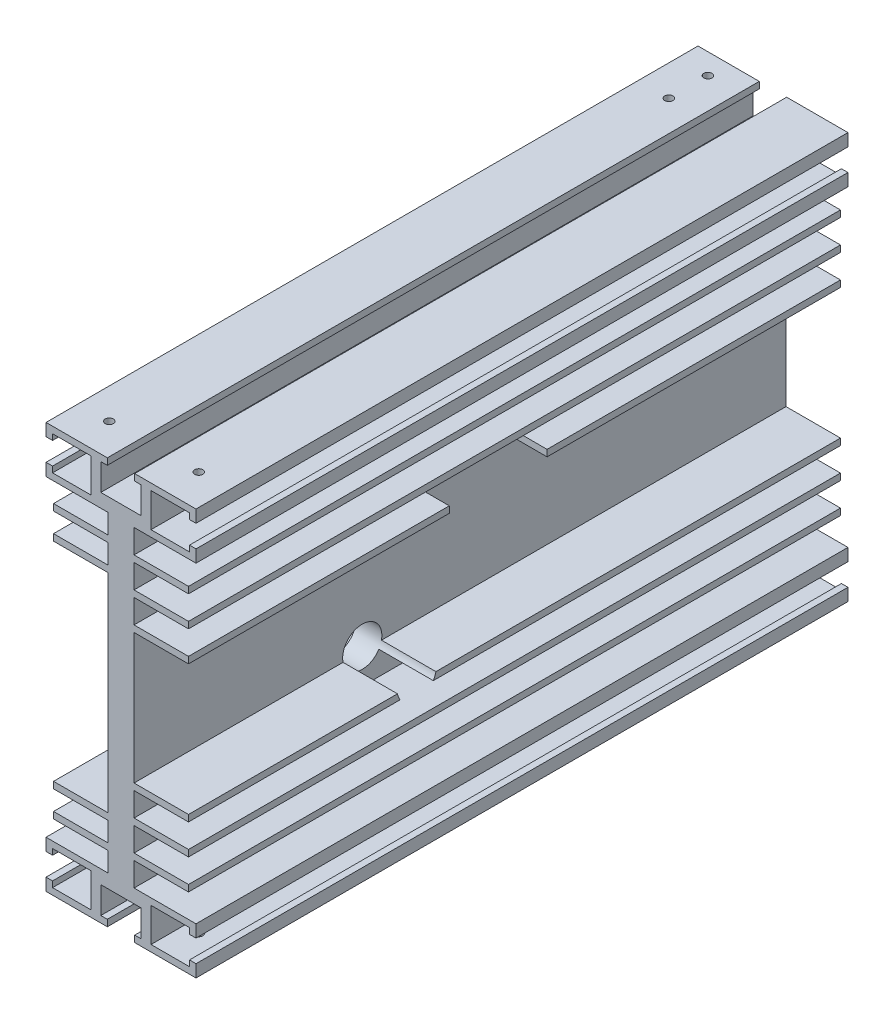
SolidWorks part; units mm, degrees
material "Alumina"
ref_plane "Plano frontal" through (0, 0, 0) normal (0, 0, 1) x (1, 0, 0)
ref_plane "Plano superior" through (0, 0, 0) normal (0, 1, 0) x (1, 0, 0)
ref_plane "Plano direito" through (0, 0, 0) normal (1, 0, 0) x (0, 0, -1)
sketch "Esboço1" plane through (0, 0, 0) normal (0, 0, 1) x (1, 0, 0)
  line L0 (-54.7403, -0.6) -> (-54.7403, 63.2)
  line L1 (-44.5403, -20.8) -> (-44.5403, -29)
  line L2 (-44.5403, -29) -> (-46.5403, -29)
  line L3 (-46.5403, -29) -> (-46.5403, -31)
  line L4 (-46.5403, -31) -> (-27.7403, -31)
  line L5 (-27.7403, -31) -> (-27.7403, -27.2)
  line L6 (-27.7403, -27.2) -> (-29.7403, -27.2)
  line L7 (-29.7403, -27.2) -> (-29.7403, -29)
  line L8 (-29.7403, -29) -> (-41.5403, -29)
  line L9 (-41.5403, -29) -> (-41.5403, -18.6)
  line L10 (-41.5403, -18.6) -> (-29.7403, -18.6)
  line L11 (-29.7403, -18.6) -> (-29.7403, -20.4)
  line L12 (-29.7403, -20.4) -> (-27.7403, -20.4)
  line L13 (-27.7403, -20.4) -> (-27.7403, -16.6)
  line L14 (-27.7403, -16.6) -> (-46.7403, -16.6)
  line L15 (-46.7403, -7.3) -> (-46.7403, 0)
  line L16 (-46.7403, -7.3) -> (-30.0403, -7.3)
  line L17 (-30.0403, -7.3) -> (-30.0403, -9.3)
  line L18 (-30.0403, -9.3) -> (-46.7403, -9.3)
  line L19 (-46.7403, -16.6) -> (-46.7403, -9.3)
  line L20 (-46.7403, 0) -> (-30.0403, 0)
  line L21 (-30.0403, 0) -> (-30.0403, 2)
  line L22 (-30.0403, 2) -> (-46.7403, 2)
  line L23 (-46.7403, 2) -> (-46.7403, 9.3)
  line L24 (-46.7403, 9.3) -> (-30.0403, 9.3)
  line L25 (-30.0403, 9.3) -> (-30.0403, 11.3)
  line L26 (-30.0403, 11.3) -> (-46.7403, 11.3)
  line L27 (-46.7403, 11.3) -> (-46.7403, 51.3)
  line L29 (-56.9403, -20.8) -> (-44.5403, -20.8)
  line L30 (-56.9403, 83.4) -> (-56.9403, 91.6)
  line L31 (-56.9403, 91.6) -> (-54.9403, 91.6)
  line L32 (-54.9403, 91.6) -> (-54.9403, 93.6)
  line L33 (-54.9403, 93.6) -> (-73.7403, 93.6)
  line L34 (-73.7403, 93.6) -> (-73.7403, 89.8)
  line L35 (-71.4403, -0.6) -> (-54.7403, -0.6)
  line L36 (-71.4403, -2.6) -> (-71.4403, -0.6)
  line L37 (-54.7403, -2.6) -> (-71.4403, -2.6)
  line L38 (-54.7403, -16.6) -> (-54.7403, -10.6)
  line L39 (-71.4403, -10.6) -> (-54.7403, -10.6)
  line L40 (-71.4403, -8.6) -> (-71.4403, -10.6)
  line L41 (-54.7403, -8.6) -> (-71.4403, -8.6)
  line L42 (-54.7403, -8.6) -> (-54.7403, -2.6)
  line L43 (-73.7403, -16.6) -> (-54.7403, -16.6)
  line L44 (-73.7403, -20.4) -> (-73.7403, -16.6)
  line L45 (-71.7403, -20.4) -> (-73.7403, -20.4)
  line L46 (-71.7403, -18.6) -> (-71.7403, -20.4)
  line L47 (-59.9403, -18.6) -> (-71.7403, -18.6)
  line L48 (-59.9403, -29) -> (-59.9403, -18.6)
  line L49 (-71.7403, -29) -> (-59.9403, -29)
  line L50 (-71.7403, -27.2) -> (-71.7403, -29)
  line L51 (-73.7403, -27.2) -> (-71.7403, -27.2)
  line L52 (-73.7403, -31) -> (-73.7403, -27.2)
  line L53 (-54.9403, -31) -> (-73.7403, -31)
  line L54 (-54.9403, -29) -> (-54.9403, -31)
  line L55 (-56.9403, -29) -> (-54.9403, -29)
  line L56 (-56.9403, -20.8) -> (-56.9403, -29)
  line L57 (-73.7403, 89.8) -> (-71.7403, 89.8)
  line L58 (-71.7403, 89.8) -> (-71.7403, 91.6)
  line L59 (-71.7403, 91.6) -> (-59.9403, 91.6)
  line L60 (-59.9403, 91.6) -> (-59.9403, 81.2)
  line L61 (-59.9403, 81.2) -> (-71.7403, 81.2)
  line L62 (-71.7403, 81.2) -> (-71.7403, 83)
  line L63 (-71.7403, 83) -> (-73.7403, 83)
  line L64 (-73.7403, 83) -> (-73.7403, 79.2)
  line L65 (-73.7403, 79.2) -> (-54.7403, 79.2)
  line L66 (-54.7403, 71.2) -> (-54.7403, 65.2)
  line L67 (-54.7403, 71.2) -> (-71.4403, 71.2)
  line L68 (-71.4403, 71.2) -> (-71.4403, 73.2)
  line L69 (-71.4403, 73.2) -> (-54.7403, 73.2)
  line L70 (-54.7403, 79.2) -> (-54.7403, 73.2)
  line L71 (-54.7403, 65.2) -> (-71.4403, 65.2)
  line L72 (-71.4403, 65.2) -> (-71.4403, 63.2)
  line L73 (-71.4403, 63.2) -> (-54.7403, 63.2)
  line L74 (-56.9403, 83.4) -> (-44.5403, 83.4)
  line L75 (-30.0403, 51.3) -> (-46.7403, 51.3)
  line L76 (-30.0403, 53.3) -> (-30.0403, 51.3)
  line L77 (-46.7403, 53.3) -> (-30.0403, 53.3)
  line L78 (-46.7403, 60.6) -> (-46.7403, 53.3)
  line L79 (-30.0403, 60.6) -> (-46.7403, 60.6)
  line L80 (-30.0403, 62.6) -> (-30.0403, 60.6)
  line L81 (-46.7403, 62.6) -> (-30.0403, 62.6)
  line L82 (-46.7403, 79.2) -> (-46.7403, 71.9)
  line L83 (-30.0403, 71.9) -> (-46.7403, 71.9)
  line L84 (-30.0403, 69.9) -> (-30.0403, 71.9)
  line L85 (-46.7403, 69.9) -> (-30.0403, 69.9)
  line L86 (-46.7403, 69.9) -> (-46.7403, 62.6)
  line L87 (-27.7403, 79.2) -> (-46.7403, 79.2)
  line L88 (-27.7403, 83) -> (-27.7403, 79.2)
  line L89 (-29.7403, 83) -> (-27.7403, 83)
  line L90 (-29.7403, 81.2) -> (-29.7403, 83)
  line L91 (-41.5403, 81.2) -> (-29.7403, 81.2)
  line L92 (-41.5403, 91.6) -> (-41.5403, 81.2)
  line L93 (-29.7403, 91.6) -> (-41.5403, 91.6)
  line L94 (-29.7403, 89.8) -> (-29.7403, 91.6)
  line L95 (-27.7403, 89.8) -> (-29.7403, 89.8)
  line L96 (-27.7403, 93.6) -> (-27.7403, 89.8)
  line L97 (-46.5403, 93.6) -> (-27.7403, 93.6)
  line L98 (-46.5403, 91.6) -> (-46.5403, 93.6)
  line L99 (-44.5403, 91.6) -> (-46.5403, 91.6)
  line L100 (-44.5403, 83.4) -> (-44.5403, 91.6)
  dimension "D1" = 2
  dimension "D2" = 3.8
  dimension "D3" = 2
  dimension "D4" = 18.8
  dimension "D5" = 3
  dimension "D6" = 2
  dimension "D7" = 2
  dimension "D8" = 2
  dimension "D9" = 3.8
  dimension "D10" = 4.2
  dimension "D11" = 19
  dimension "D12" = 16.7
  dimension "D13" = 7.3
  dimension "D14" = 2
  dimension "D15" = 6
  dimension "D16" = 6
  dimension "D17" = 10.4
  dimension "D18" = 40
  dimension "D19" = 63.8
extrude "Ressalto-extrusão1" add sketch "Esboço1" along normal blind 200
ref_plane "Plano1" through (0, 0, 100) normal (0, 0, 1) x (1, 0, 0)
ref_plane "Plano2" through (0, 31.3, 0) normal (0, -1, 0) x (1, 0, 0)
sketch "Esboço4" plane through (-54.7403, 0, 0) normal (-1, 0, 0) x (0, 0, 1)
  line L0 (200, 93.6) -> (0, 93.6) construction
  line L1 (0, 63.2) -> (0, -0.6) construction
  circle A0 centre (104, 50.1) radius 1.825
  dimension "D1" = 43.5
  dimension "D2" = 104
extrude "Corte-extrusão3" cut sketch "Esboço4" against normal up to next
sketch "Esboço6" plane through (-54.7403, 0, 0) normal (-1, 0, 0) x (0, 0, 1)
  line L0 (200, -31) -> (0, -31) construction
  line L3 (0, 63.2) -> (0, -0.6) construction
  circle A0 centre (130, 12.5) radius 6.0125
  dimension "D1" = 12.025
  dimension "D2" = 43.5
  dimension "D3" = 130
extrude "Corte-extrusão5" cut sketch "Esboço6" against normal up to next
hole_wizard "Broca de rosquear para tarraxa de M3x0.53" positions "Esboço13" profile "Esboço12" hole size "M3x0.5" standard "Métrico Ansi" end condition up to next
sketch "Esboço13" plane through (-54.7403, 0, 0) normal (-1, 0, 0) x (0, 0, 1)
  line L0 (200, 65.2) -> (0, 65.2) construction
  line L1 (0, 63.2) -> (0, -0.6) construction
  line L2 (200, -0.6) -> (0, -0.6) construction
  point P0 (6, 5.9)
  point P1 (6, 58.2)
  dimension "D1" = 7
  dimension "D2" = 6
  dimension "D3" = 6
  dimension "D4" = 6.5
sketch "Esboço12" plane through (-54.7403, 5.9, 6) normal (0, 1, 0) x (0, 0, 1)
  line L0 (0, 0) -> (0, 8)
  line L1 (0, 8) -> (1.25, 8)
  line L2 (1.25, 8) -> (1.25, 0)
  line L5 (1.25, 0) -> (0, 0)
  line L11 (0, -6.35) -> (0, 107.95) construction
  dimension "Thru Hole Dia." = 2.5
  dimension "Thru Hole Depth" = 8
cosmetic thread "Representação de rosca2" parameters "D1"=5, "D2"=3
hole_wizard "Broca de rosquear para tarraxa de M3x0.54" positions "Esboço15" profile "Esboço14" hole size "M3x0.5" standard "Métrico Ansi"
sketch "Esboço15" plane through (-54.7403, 0, 0) normal (-1, 0, 0) x (0, 0, 1)
  line L0 (200, 63.2) -> (200, -0.6) construction
  line L1 (200, 93.6) -> (0, 93.6) construction
  point P0 (96, 50.1)
  dimension "D1" = 104
  dimension "D2" = 43.5
sketch "Esboço14" plane through (-54.7403, 50.1, 96) normal (0, 1, 0) x (0, 0, 1)
  line L0 (0, 0) -> (0, 8)
  line L1 (0, 8) -> (1.25, 8)
  line L2 (1.25, 8) -> (1.25, 0)
  line L5 (1.25, 0) -> (0, 0)
  line L11 (0, -6.35) -> (0, 107.95) construction
  dimension "Thru Hole Dia." = 2.5
  dimension "Thru Hole Depth" = 8
hole_wizard "Broca de rosquear para tarraxa de M3x0.56" positions "Esboço21" profile "Esboço20" hole size "M3x0.5" standard "Métrico Ansi"
sketch "Esboço21" plane through (0, 93.6, 0) normal (0, 1, 0) x (-1, 0, 0)
  line L0 (73.7403, 200) -> (73.7403, 0) construction
  line L1 (54.9403, 200) -> (73.7403, 200) construction
  point P0 (64.3403, 190)
  point P1 (37.1403, 189.76)
  dimension "D1" = 9.4
  dimension "D2" = 10
sketch "Esboço20" plane through (-64.3403, 93.6, 190) normal (1, 0, 0) x (0, 0, 1)
  line L0 (0, 0) -> (0, 2)
  line L1 (0, 2) -> (1.25, 2)
  line L2 (1.25, 2) -> (1.25, 0)
  line L5 (1.25, 0) -> (0, 0)
  line L11 (0, -6.35) -> (0, 107.95) construction
  dimension "Thru Hole Dia." = 2.5
  dimension "Thru Hole Depth" = 2
cosmetic thread "Representação de rosca1" parameters "D2"=3
hole_wizard "Broca de rosquear para tarraxa de M3x0.57" positions "Esboço23" profile "Esboço22" hole size "M3x0.5" standard "Métrico Ansi"
sketch "Esboço23" plane through (0, 93.6, 0) normal (0, 1, 0) x (-1, 0, 0)
  point P0 (64.3403, 18.36)
  point P1 (64.3403, 6.36)
sketch "Esboço22" plane through (-64.3403, 93.6, 18.36) normal (1, 0, 0) x (0, 0, 1)
  line L0 (0, 0) -> (0, 2)
  line L1 (0, 2) -> (1.25, 2)
  line L2 (1.25, 2) -> (1.25, 0)
  line L5 (1.25, 0) -> (0, 0)
  line L11 (0, -6.35) -> (0, 107.95) construction
  dimension "Thru Hole Dia." = 2.5
  dimension "Thru Hole Depth" = 2
hole_wizard "Broca de rosquear para tarraxa de M3x0.58" positions "Esboço25" profile "Esboço24" hole size "M3x0.5" standard "Métrico Ansi"
sketch "Esboço25" plane through (0, -31, 0) normal (0, -1, 0) x (1, 0, 0)
  point P0 (-64.3403, 18.36)
  point P1 (-64.3403, 6.36)
sketch "Esboço24" plane through (-64.3403, -31, 18.36) normal (1, 0, 0) x (0, 0, -1)
  line L0 (0, 0) -> (0, 2)
  line L1 (0, 2) -> (1.25, 2)
  line L2 (1.25, 2) -> (1.25, 0)
  line L5 (1.25, 0) -> (0, 0)
  line L11 (0, -6.35) -> (0, 107.95) construction
  dimension "Thru Hole Dia." = 2.5
  dimension "Thru Hole Depth" = 2
cosmetic thread "Representação de rosca4" parameters "D1"=2, "D2"=3
cosmetic thread "Representação de rosca5" parameters "D1"=2, "D2"=3
sketch "Esboço26" plane through (-30.0403, 0, 0) normal (1, 0, 0) x (0, 0, -1)
  line L0 (-200, 53.3) -> (0, 53.3) construction
  line L1 (-120, 53.3) -> (-90, 53.3)
  line L2 (-120, 53.3) -> (-120, 51.3)
  line L3 (-120, 51.3) -> (-90, 51.3)
  line L4 (-90, 53.3) -> (-90, 51.3)
  line L5 (-102.625, 51.3) -> (0, 51.3) construction
  line L6 (-200, 11.3) -> (-200, 51.3) construction
  dimension "D1" = 30
  dimension "D2" = 80
extrude "Corte-extrusão6" cut sketch "Esboço26" against normal up to vertex
hole_wizard "Broca de rosquear para tarraxa de M3x0.59" positions "Esboço28" profile "Esboço27" hole size "M3x0.5" standard "Métrico Ansi"
sketch "Esboço28" plane through (0, -31, 0) normal (0, -1, 0) x (1, 0, 0)
  point P0 (-64.3403, 189.76)
  point P1 (-37.1403, 189.76)
sketch "Esboço27" plane through (-64.3403, -31, 189.76) normal (1, 0, 0) x (0, 0, -1)
  line L0 (0, 0) -> (0, 2)
  line L1 (0, 2) -> (1.25, 2)
  line L2 (1.25, 2) -> (1.25, 0)
  line L5 (1.25, 0) -> (0, 0)
  line L11 (0, -6.35) -> (0, 107.95) construction
  dimension "Thru Hole Dia." = 2.5
  dimension "Thru Hole Depth" = 2
cosmetic thread "Representação de rosca3" parameters "D1"=2, "D2"=3
equation "\"D1@Esboço6\"=\"H_Barra@Inversor3.SLDASM\""
equation "\"D1@Esboço15\" = \"Barramento_sy@Inversor3.SLDASM\""
equation "\"D2@Esboço15\" = \"Barramento_sx@Inversor3.SLDASM\""
equation "\"D1@Esboço4\" = \"Barramento_sx@Inversor3.SLDASM\""
equation "\"D2@Esboço4\" = \"Barramento_sy@Inversor3.SLDASM\""
equation "\"D2@Esboço6\" = \"Barramento_gx@Inversor3.SLDASM\""
equation "\"D3@Esboço6\" = \"Barramento_gy@Inversor3.SLDASM\""
